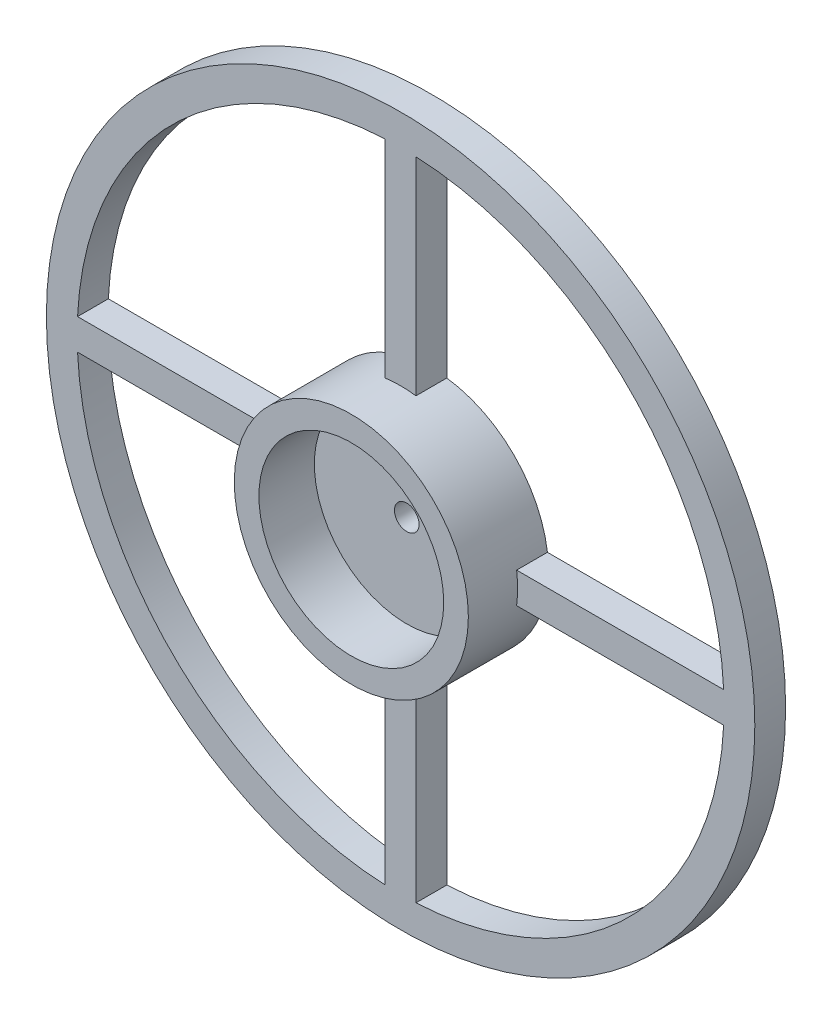
SolidWorks part; units mm, degrees
ref_plane "Front Plane" through (0, 0, 0) normal (0, 0, 1) x (1, 0, 0)
ref_plane "Top Plane" through (0, 0, 0) normal (0, 1, 0) x (1, 0, 0)
ref_plane "Right Plane" through (0, 0, 0) normal (1, 0, 0) x (0, 0, -1)
sketch "Sketch1" plane through (0, 0, 0) normal (0, 0, 1) x (1, 0, 0)
  line L0 (0, 57.5) -> (0, 55) construction
  line L1 (0, -57.5) -> (57.5, 0) construction
  line L2 (57.5, 0) -> (-57.5, 0) construction
  line L3 (-57.5, 0) -> (0, -57.5) construction
  line L4 (-2.5, 52.4404) -> (-2.5, 14.7902)
  line L5 (2.5, 52.4404) -> (2.5, 14.7902)
  line L6 (-2.5, -52.4404) -> (-2.5, -14.7902)
  line L7 (2.5, -52.4404) -> (2.5, -14.7902)
  line L8 (-2.5, 33.6153) -> (0, 33.6153) construction
  line L9 (0, 33.6153) -> (2.5, 33.6153) construction
  line L12 (52.4404, -2.5) -> (14.7902, -2.5)
  line L13 (52.4404, 2.5) -> (14.7902, 2.5)
  line L14 (-52.4404, 2.5) -> (-14.7902, 2.5)
  line L15 (-52.4404, -2.5) -> (-14.7902, -2.5)
  line L16 (-2.5, -52.4404) -> (-2.5, -14.7902)
  line L17 (2.5, -52.4404) -> (2.5, -14.7902)
  line L18 (2.5, 52.4404) -> (2.5, 14.7902)
  line L19 (-2.5, 52.4404) -> (-2.5, 14.7902)
  line L20 (-52.4404, 2.5) -> (-14.7902, 2.5)
  line L21 (-52.4404, -2.5) -> (-14.7902, -2.5)
  line L22 (52.4404, -2.5) -> (14.7902, -2.5)
  line L23 (52.4404, 2.5) -> (14.7902, 2.5)
  line L24 (0, 27.5) -> (0, -27.5) construction
  line L25 (0, -55) -> (0, -57.5) construction
  circle A0 centre (0, 0) radius 55 construction
  circle A1 centre (0, 0) radius 57.5
  arc A2 (-2.5, 52.4404) -> (-52.4404, 2.5) centre (0, 0) ccw
  arc A3 (-2.5, 14.7902) -> (-14.7902, 2.5) centre (0, 0) ccw
  arc A4 (-2.5, 52.4404) -> (-52.4404, 2.5) centre (0, 0) ccw
  arc A5 (-2.5, 52.4404) -> (-52.4404, 2.5) centre (0, 0) ccw
  arc A6 (-2.5, 52.4404) -> (-52.4404, 2.5) centre (0, 0) ccw
  arc A7 (-14.7902, -2.5) -> (-2.5, -14.7902) centre (0, 0) ccw
  arc A8 (-52.4404, -2.5) -> (-2.5, -52.4404) centre (0, 0) ccw
  arc A9 (-52.4404, -2.5) -> (-2.5, -52.4404) centre (0, 0) ccw
  arc A10 (-52.4404, -2.5) -> (-2.5, -52.4404) centre (0, 0) ccw
  arc A11 (-52.4404, -2.5) -> (-2.5, -52.4404) centre (0, 0) ccw
  arc A12 (14.7902, 2.5) -> (2.5, 14.7902) centre (0, 0) ccw
  arc A13 (52.4404, 2.5) -> (2.5, 52.4404) centre (0, 0) ccw
  arc A14 (52.4404, 2.5) -> (2.5, 52.4404) centre (0, 0) ccw
  arc A15 (52.4404, 2.5) -> (2.5, 52.4404) centre (0, 0) ccw
  arc A16 (52.4404, 2.5) -> (2.5, 52.4404) centre (0, 0) ccw
  arc A17 (2.5, -14.7902) -> (14.7902, -2.5) centre (0, 0) ccw
  arc A18 (2.5, -52.4404) -> (52.4404, -2.5) centre (0, 0) ccw
  arc A19 (2.5, -52.4404) -> (52.4404, -2.5) centre (0, 0) ccw
  arc A20 (2.5, -52.4404) -> (52.4404, -2.5) centre (0, 0) ccw
  arc A21 (2.5, -52.4404) -> (52.4404, -2.5) centre (0, 0) ccw
  circle A22 centre (0, 0) radius 2
  circle A23 centre (0, 0) radius 19
  point P54 (0, 0)
  dimension "D1" = 110
  dimension "D2" = 2.5
  dimension "D3" = 2.5
  dimension "D4" = 30
  dimension "D7" = 4
  dimension "D8" = 4
  dimension "D9" = 15
  dimension "D5" = 5
  dimension "D6" = 4
extrude "Boss-Extrude1" add sketch "Sketch1" along normal blind 5 contours A1 A23 L5 A13 L13 L12 A18 L7 L6 A8 L15 L14 A2 L4 | L19 A23 L20 A3 | L21 A23 L16 A7 | L18 A23 L19 A3 L20 L21 A7 L16 L17 A17 L22 L23 A12 A22 | L23 A23 L18 A12 | L17 A23 L22 A17
sketch "Sketch2" plane through (0, 0, 5) normal (0, 0, 1) x (1, 0, 0)
  circle A0 centre (0, 0) radius 15
extrude "Cut-Extrude1" cut sketch "Sketch2" against normal blind 1
sketch "Sketch3" plane through (0, 0, 5) normal (0, 0, 1) x (1, 0, 0)
  circle A0 centre (0, 0) radius 15 construction
  circle A5 centre (0, 0) radius 15
  circle A6 centre (0, 0) radius 19
extrude "Boss-Extrude3" add sketch "Sketch3" along normal blind 8
